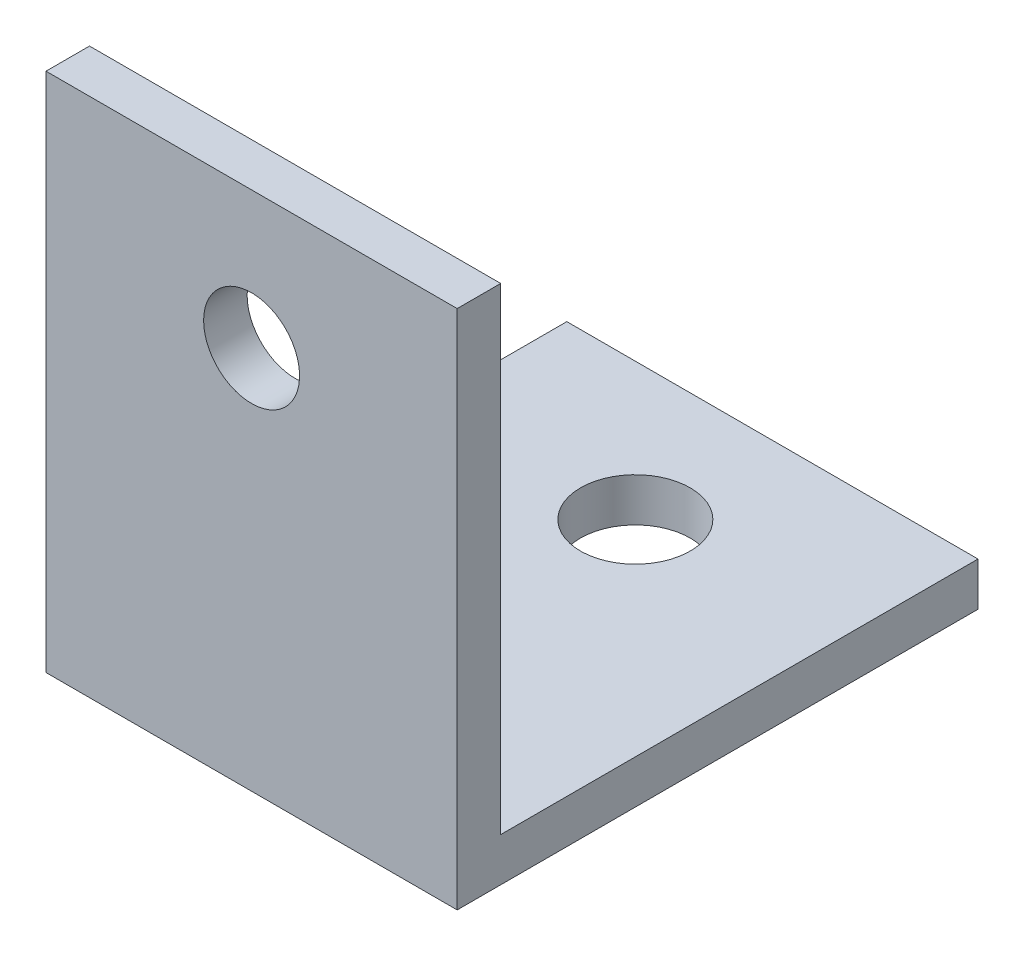
SolidWorks part; units mm, degrees
ref_plane "Front Plane" through (0, 0, 0) normal (0, 0, 1) x (1, 0, 0)
ref_plane "Top Plane" through (0, 0, 0) normal (0, 1, 0) x (1, 0, 0)
ref_plane "Right Plane" through (0, 0, 0) normal (1, 0, 0) x (0, 0, -1)
sketch "Sketch1" plane through (0, 0, 0) normal (0, 0, 1) x (1, 0, 0)
  line L1 (0, 0) -> (30, 0)
  line L2 (0, 0) -> (0, 38)
  line L3 (0, 38) -> (30, 38)
  line L4 (30, 0) -> (30, 38)
  dimension "D1" = 30
  dimension "D2" = 38
extrude "Boss-Extrude1" add sketch "Sketch1" along normal blind 3.175
sketch "Sketch2" plane through (0, 0, 0) normal (0, 0, -1) x (-1, 0, 0)
  line L0 (0, 38) -> (0, 0) construction
  line L1 (-30, 0) -> (0, 0)
  line L2 (-30, 0) -> (-30, 3.175)
  line L3 (-30, 3.175) -> (0, 3.175)
  line L4 (0, 0) -> (0, 3.175)
  dimension "D1" = 3.175
extrude "Boss-Extrude2" add sketch "Sketch2" along normal blind 34.825
sketch "Sketch3" plane through (0, 0, 0) normal (0, 0, -1) x (-1, 0, 0)
  line L0 (-30, 38) -> (0, 38) construction
  line L1 (-30, 3.175) -> (-30, 38) construction
  circle A0 centre (-15, 28) radius 4
  dimension "D1" = 8
  dimension "D2" = 10
  dimension "D3" = 15
extrude "Cut-Extrude1" cut sketch "Sketch3" against normal through all
sketch "Sketch4" plane through (0, 3.175, 0) normal (0, 1, 0) x (1, 0, 0)
  line L0 (0, 34.825) -> (30, 34.825) construction
  line L1 (30, 34.825) -> (30, 0) construction
  circle A0 centre (15, 24.825) radius 4
  dimension "D1" = 8
  dimension "D2" = 10
  dimension "D3" = 15
extrude "Cut-Extrude2" cut sketch "Sketch4" against normal through all
sketch "Croquis4" plane through (0, 0, 0) normal (0, 0, -1) x (-1, 0, 0)
  circle A0 centre (-15, 28) radius 4
  circle A1 centre (-15, 28) radius 3.5
extrude "Saliente-Extruir2" add sketch "Croquis4" against normal blind 5
sketch "Croquis5" plane through (0, 0, 0) normal (-1, 0, 0) x (0, 0, 1)
  line L0 (3.175, 38) -> (3.175, 0) construction
  line L1 (3.175, 32.6359) -> (7.154, 32.6359)
  line L2 (3.175, 32.6359) -> (3.175, 22.5356)
  line L3 (3.175, 22.5356) -> (7.154, 22.5356)
  line L4 (7.154, 32.6359) -> (7.154, 22.5356)
extrude "Cortar-Extruir1" cut sketch "Croquis5" against normal blind 36
